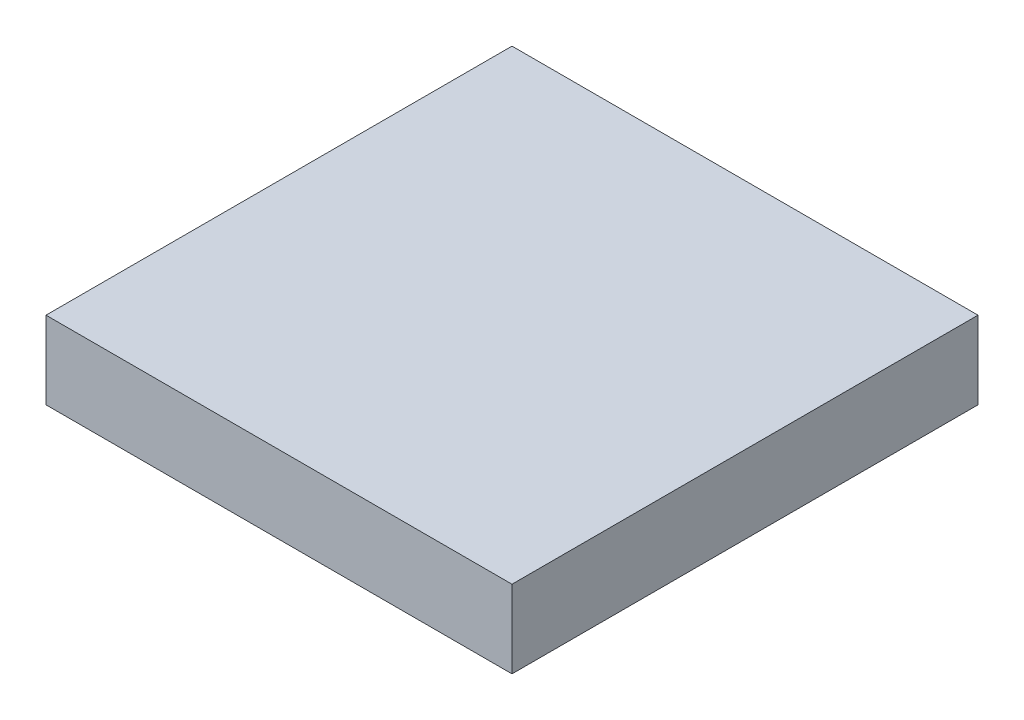
SolidWorks part; units mm, degrees
ref_plane "Front Plane" through (0, 0, 0) normal (0, 0, 1) x (1, 0, 0)
ref_plane "Top Plane" through (0, 0, 0) normal (0, 1, 0) x (1, 0, 0)
ref_plane "Right Plane" through (0, 0, 0) normal (1, 0, 0) x (0, 0, -1)
sketch "Sketch1" plane through (0, 0, 0) normal (0, 1, 0) x (1, 0, 0)
  line L1 (0, 0) -> (3000, 0)
  line L2 (0, 0) -> (0, 3000)
  line L3 (0, 3000) -> (3000, 3000)
  line L4 (3000, 0) -> (3000, 3000)
  dimension "D1" = 3000
  dimension "D2" = 3000
extrude "Boss-Extrude1" add sketch "Sketch1" along normal blind 500
